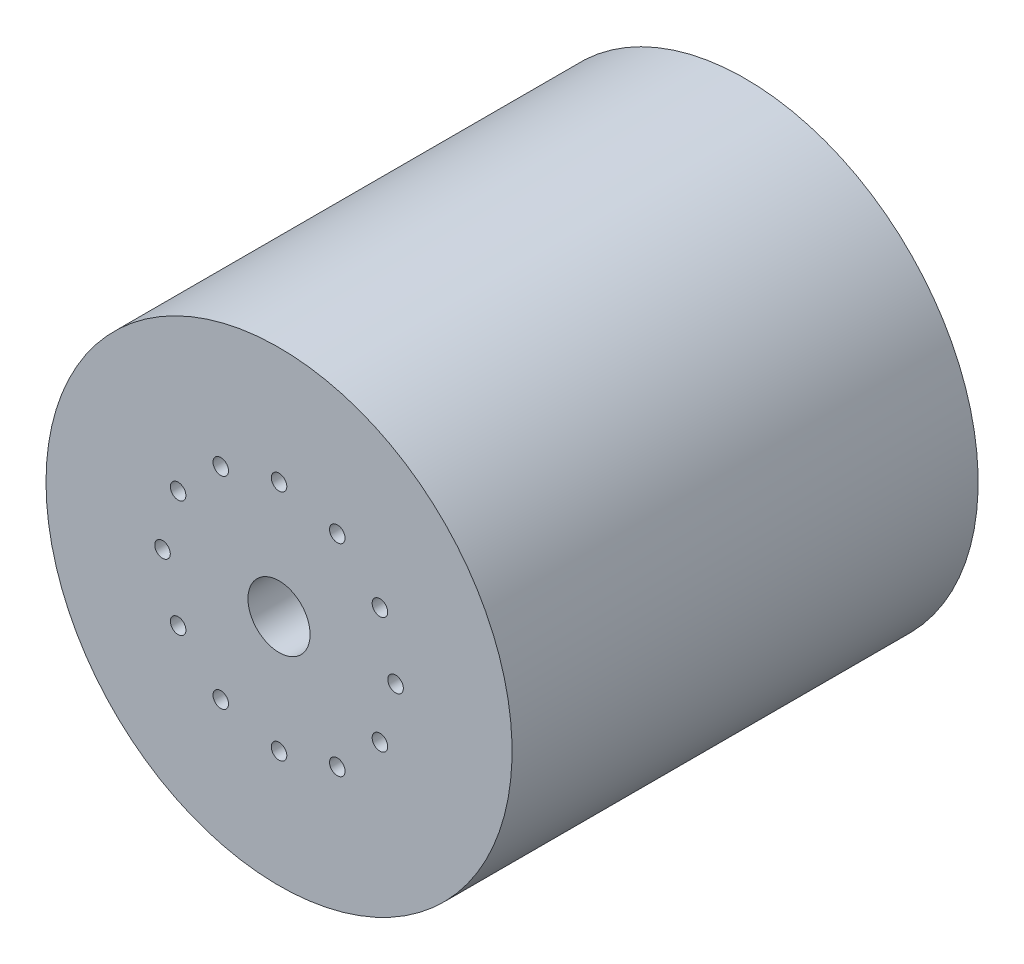
SolidWorks part; units mm, degrees
material "Ceramic Porcelain"
ref_plane "Front Plane" through (0, 0, 0) normal (0, 0, 1) x (1, 0, 0)
ref_plane "Top Plane" through (0, 0, 0) normal (0, 1, 0) x (1, 0, 0)
ref_plane "Right Plane" through (0, 0, 0) normal (1, 0, 0) x (0, 0, -1)
sketch "Sketch1" plane through (0, 0, 0) normal (0, 0, 1) x (1, 0, 0)
  circle A0 centre (0, 0) radius 38.1
  circle A1 centre (0, 0) radius 35.56
  circle A2 centre (0, 0) radius 5.08
  circle A3 centre (0, 0) radius 7.62
  circle A4 centre (0, 19.05) radius 1.27
  circle A5 centre (9.525, 16.4978) radius 1.27
  circle A6 centre (16.4978, 9.525) radius 1.27
  circle A7 centre (19.05, 0) radius 1.27
  circle A8 centre (16.4978, -9.525) radius 1.27
  circle A9 centre (9.525, -16.4978) radius 1.27
  circle A10 centre (0, -19.05) radius 1.27
  circle A11 centre (-9.525, -16.4978) radius 1.27
  circle A12 centre (-16.4978, -9.525) radius 1.27
  circle A13 centre (-19.05, 0) radius 1.27
  circle A14 centre (-16.4978, 9.525) radius 1.27
  circle A15 centre (-9.525, 16.4978) radius 1.27
  point P33 (0, 0)
  dimension "D1" = 12
extrude "Boss-Extrude1" add sketch "Sketch1" along normal blind 76.2 contours A0 A1 | A1 A15 A14 A13 A12 A11 A10 A9 A8 A7 A6 A5 A4 A3 | A3 A2
sketch "Sketch2" [suppressed] plane through (0, 0, 76.2) normal (0, 0, 1) x (1, 0, 0)
  circle A0 centre (0, 0) radius 7.62
  circle A1 centre (0, 0) radius 35.56
  circle A2 centre (0, 0) radius 38.1 construction
sketch "Sketch3" plane through (0, 0, 0) normal (0, 0, -1) x (-1, 0, 0)
  circle A0 centre (0, 0) radius 7.62
  circle A1 centre (0, 0) radius 35.56
  circle M2 centre (9.525, 16.4978) radius 1.27
  circle M3 centre (16.4978, 9.525) radius 1.27
  circle M4 centre (19.05, 0) radius 1.27
  circle M5 centre (16.4978, -9.525) radius 1.27
  circle M6 centre (9.525, -16.4978) radius 1.27
  circle M7 centre (0, -19.05) radius 1.27
  circle M8 centre (-9.525, -16.4978) radius 1.27
  circle M9 centre (-16.4978, -9.525) radius 1.27
  circle M10 centre (-19.05, 0) radius 1.27
  circle M11 centre (-16.4978, 9.525) radius 1.27
  circle M12 centre (-9.525, 16.4978) radius 1.27
  circle M13 centre (0, 19.05) radius 1.27
extrude "Cut-Extrude1" cut sketch "Sketch3" against normal blind 73.66 contours A1 A0 M3 M5 M7 M9 M11 M13 M12 M10 M8 M6 M4 M2
scale "Scale3" scale about centroid uniform scaling yes scale factor 29
scale "Scale4" scale about centroid uniform scaling yes scale factor 0.95
